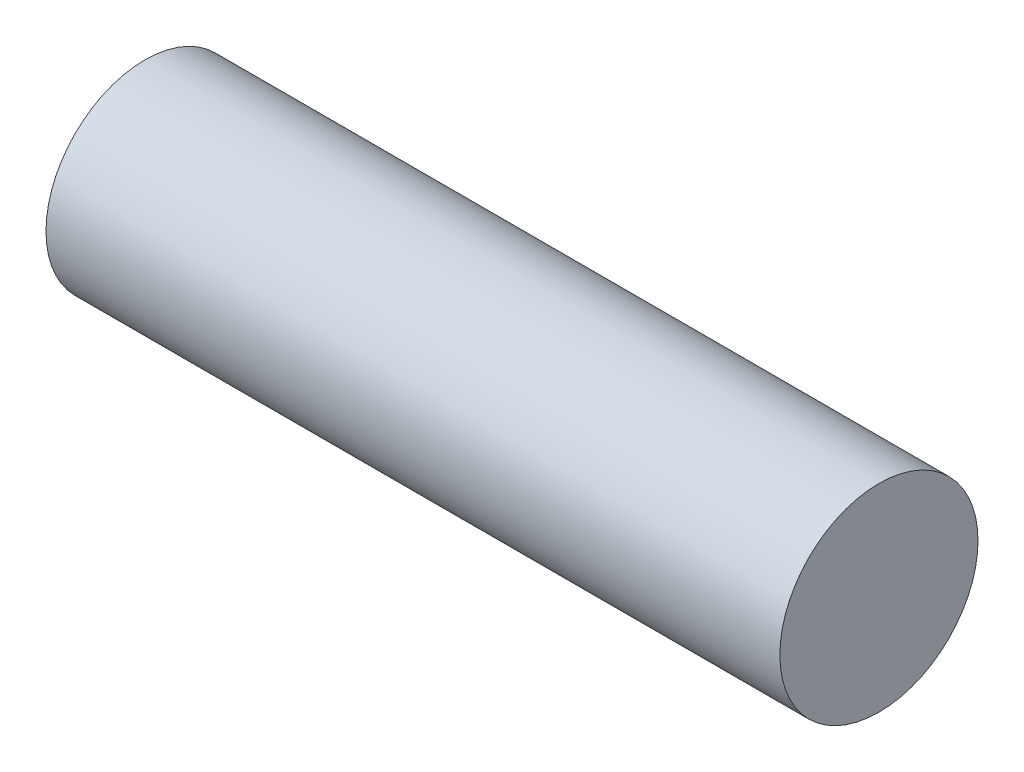
SolidWorks part; units mm, degrees
ref_plane "Front Plane" through (0, 0, 0) normal (0, 0, 1) x (1, 0, 0)
ref_plane "Top Plane" through (0, 0, 0) normal (0, 1, 0) x (1, 0, 0)
ref_plane "Right Plane" through (0, 0, 0) normal (1, 0, 0) x (0, 0, -1)
sketch "Sketch1" plane through (0, 0, 0) normal (1, 0, 0) x (0, 0, -1)
  circle A0 centre (0, 0) radius 6
  dimension "D1" = 12
extrude "Boss-Extrude1" add sketch "Sketch1" along normal blind 44.45
